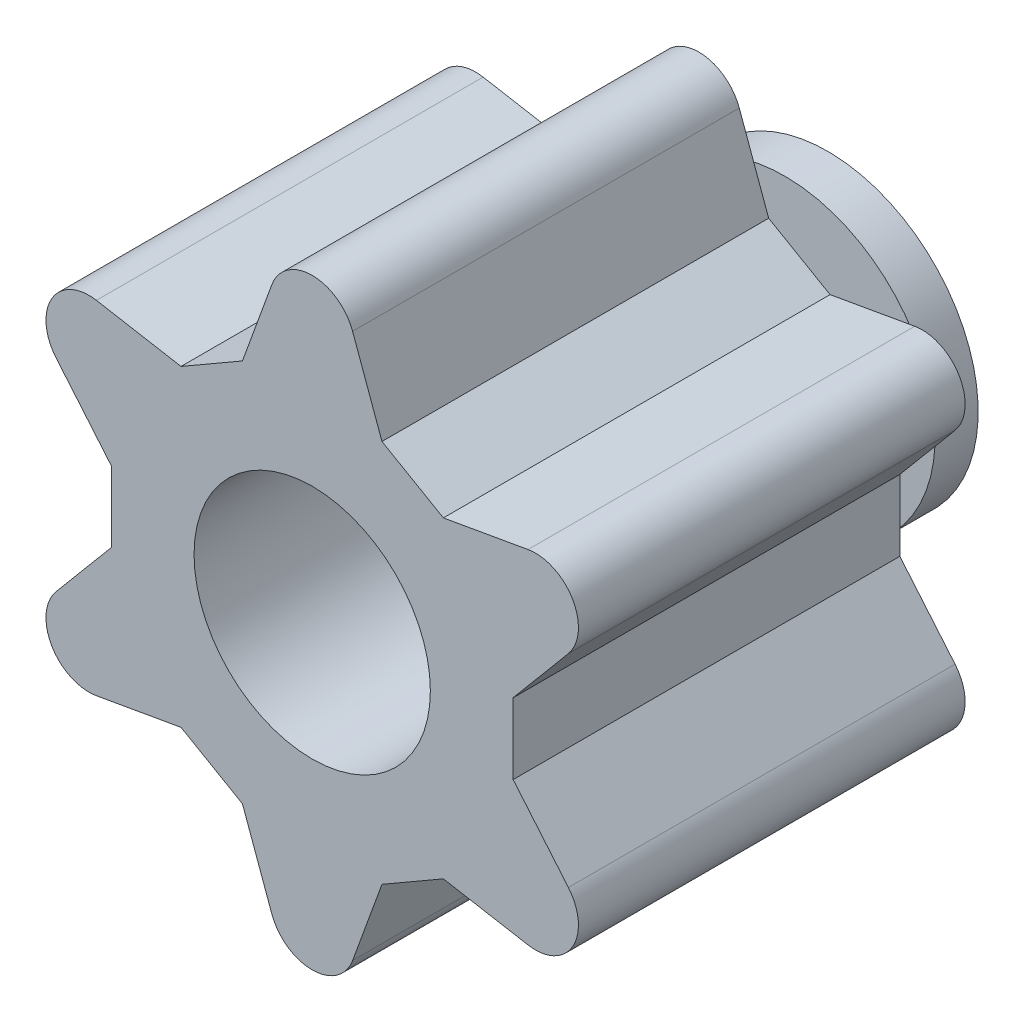
SolidWorks part; units mm, degrees
ref_plane "Front Plane" through (0, 0, 0) normal (0, 0, 1) x (1, 0, 0)
ref_plane "Top Plane" through (0, 0, 0) normal (0, 1, 0) x (1, 0, 0)
ref_plane "Right Plane" through (0, 0, 0) normal (1, 0, 0) x (0, 0, -1)
sketch "Sketch1" plane through (0, 0, 0) normal (0, 0, 1) x (1, 0, 0)
  line L0 (-1.6237, 4.4626) -> (-0.9397, 6.342)
  line L1 (2.75, -1.5877) -> (2.75, 1.5877)
  line L2 (2.75, 1.5877) -> (0, 3.1754)
  line L3 (0, 3.1754) -> (-2.75, 1.5877)
  line L4 (-2.75, 1.5877) -> (-2.75, -1.5877)
  line L5 (-2.75, -1.5877) -> (0, -3.1754)
  line L6 (0, -3.1754) -> (2.75, -1.5877)
  line L7 (0.9397, 6.342) -> (1.6237, 4.4626)
  line L8 (3.0529, 3.6375) -> (5.0225, 3.9848)
  line L9 (5.9622, 2.3572) -> (4.6766, 0.8251)
  line L10 (4.6766, -0.8251) -> (5.9622, -2.3572)
  line L11 (5.0225, -3.9848) -> (3.0529, -3.6375)
  line L12 (1.6237, -4.4626) -> (0.9397, -6.342)
  line L13 (-0.9397, -6.342) -> (-1.6237, -4.4626)
  line L14 (-3.0529, -3.6375) -> (-5.0225, -3.9848)
  line L15 (-5.9622, -2.3572) -> (-4.6766, -0.8251)
  line L16 (-4.6766, 0.8251) -> (-5.9622, 2.3572)
  line L17 (-5.0225, 3.9848) -> (-3.0529, 3.6375)
  line L18 (-3.0529, 3.6375) -> (-1.6237, 4.4626)
  line L19 (1.6237, 4.4626) -> (3.0529, 3.6375)
  line L20 (4.6766, 0.8251) -> (4.6766, -0.8251)
  line L21 (3.0529, -3.6375) -> (1.6237, -4.4626)
  line L22 (-1.6237, -4.4626) -> (-3.0529, -3.6375)
  line L23 (-4.6766, -0.8251) -> (-4.6766, 0.8251)
  circle A0 centre (0, 0) radius 2.75 construction
  arc A2 (-0.9397, 6.342) -> (0.9397, 6.342) centre (0, 6) cw
  arc A3 (5.0225, 3.9848) -> (5.9622, 2.3572) centre (5.1962, 3) cw
  arc A4 (5.9622, -2.3572) -> (5.0225, -3.9848) centre (5.1962, -3) cw
  arc A5 (0.9397, -6.342) -> (-0.9397, -6.342) centre (0, -6) cw
  arc A6 (-5.0225, -3.9848) -> (-5.9622, -2.3572) centre (-5.1962, -3) cw
  arc A7 (-5.9622, 2.3572) -> (-5.0225, 3.9848) centre (-5.1962, 3) cw
  point P13 (-6.0622, 3.5)
  point P16 (6.0622, -3.5)
  point P41 (-4.6766, 0)
  point P42 (-2.75, 0)
  point P43 (4.6766, 0)
  point P44 (2.75, 0)
  dimension "D1" = 5.5
  dimension "D2" = 1
  dimension "D3" = 14
  dimension "D5" = 40
  dimension "D6" = 2
  dimension "D4" = 6
extrude "Boss-Extrude1" add sketch "Sketch1" along normal blind 9
ref_plane "Plane1" through (0, 0, 2.5) normal (0, 0, 1) x (1, 0, 0)
sketch "Sketch5" plane through (0, 0, 2.5) normal (0, 0, -1) x (-1, 0, 0)
  line L0 (-2.75, 1.5877) -> (0, 3.1754) construction
  line L1 (-2.75, -1.5877) -> (-2.75, 1.5877) construction
  line L2 (0, -3.1754) -> (-2.75, -1.5877) construction
  line L3 (2.75, -1.5877) -> (0, -3.1754) construction
  line L4 (2.75, 1.5877) -> (2.75, -1.5877) construction
  line L5 (0, 3.1754) -> (2.75, 1.5877) construction
  line L6 (-2.75, 1.5877) -> (0, 3.1754)
  line L7 (-2.75, -1.5877) -> (-2.75, 1.5877)
  line L8 (0, -3.1754) -> (-2.75, -1.5877)
  line L9 (2.75, -1.5877) -> (0, -3.1754)
  line L10 (2.75, 1.5877) -> (2.75, -1.5877)
  line L11 (0, 3.1754) -> (2.75, 1.5877)
  circle A0 centre (0, 0) radius 1.4
  dimension "D1" = 2.8
extrude "Boss-Extrude2" add sketch "Sketch5" against normal up to surface (6.5 mm away) up to face at (0, 0, 9)
sketch "Sketch6" plane through (0, 0, 9) normal (0, 0, 1) x (1, 0, 0)
  circle A0 centre (0, 0) radius 2.75
  dimension "D1" = 5.5
extrude "Cut-Extrude1" cut sketch "Sketch6" against normal offset from surface (5 mm away) 4 up to face at (0, 0, 0)
ref_plane "Plane2" through (0, 0, -2) normal (0, 0, -1) x (-1, 0, 0)
sketch "Sketch9" plane through (0, 0, -2) normal (0, 0, -1) x (-1, 0, 0)
  circle A0 centre (0, 0) radius 1.5
  circle A1 centre (0, 0) radius 3.5
  dimension "D1" = 3
  dimension "D2" = 7
extrude "Boss-Extrude3" add sketch "Sketch9" along normal blind 1 separate body
